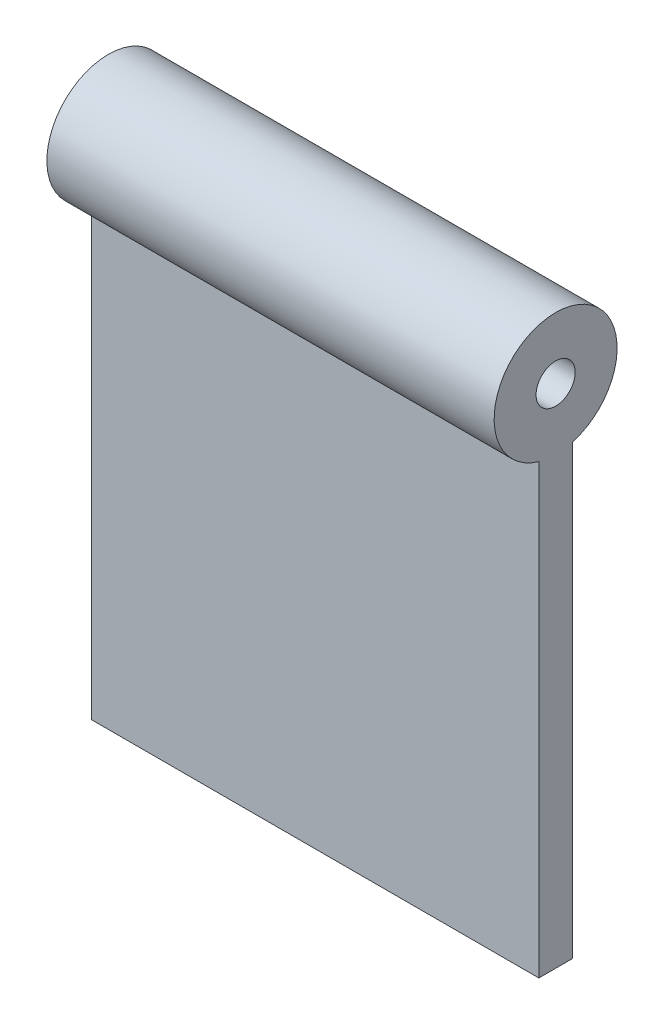
SolidWorks part; units mm, degrees
ref_plane "前视基准面" through (0, 0, 0) normal (0, 0, 1) x (1, 0, 0)
ref_plane "上视基准面" through (0, 0, 0) normal (0, 1, 0) x (1, 0, 0)
ref_plane "右视基准面" through (0, 0, 0) normal (1, 0, 0) x (0, 0, -1)
sketch "草图1" plane through (0, 0, 0) normal (1, 0, 0) x (0, 0, -1)
  line L0 (0, 0) -> (0, -9.0583) construction
  line L1 (0.3, -1.0583) -> (0.3, -9.0583)
  line L2 (0.3, -9.0583) -> (-0.3, -9.0583)
  line L3 (-0.3, -9.0583) -> (-0.3, -1.0583)
  arc A0 (0.3, -1.0583) -> (-0.3, -1.0583) centre (0, 0) ccw
  circle A1 centre (0, 0) radius 0.35
  dimension "D1" = 0.7
  dimension "D2" = 2.2
  dimension "D3" = 0.6
  dimension "D4" = 8
extrude "凸台-拉伸1" add sketch "草图1" along normal blind 8
